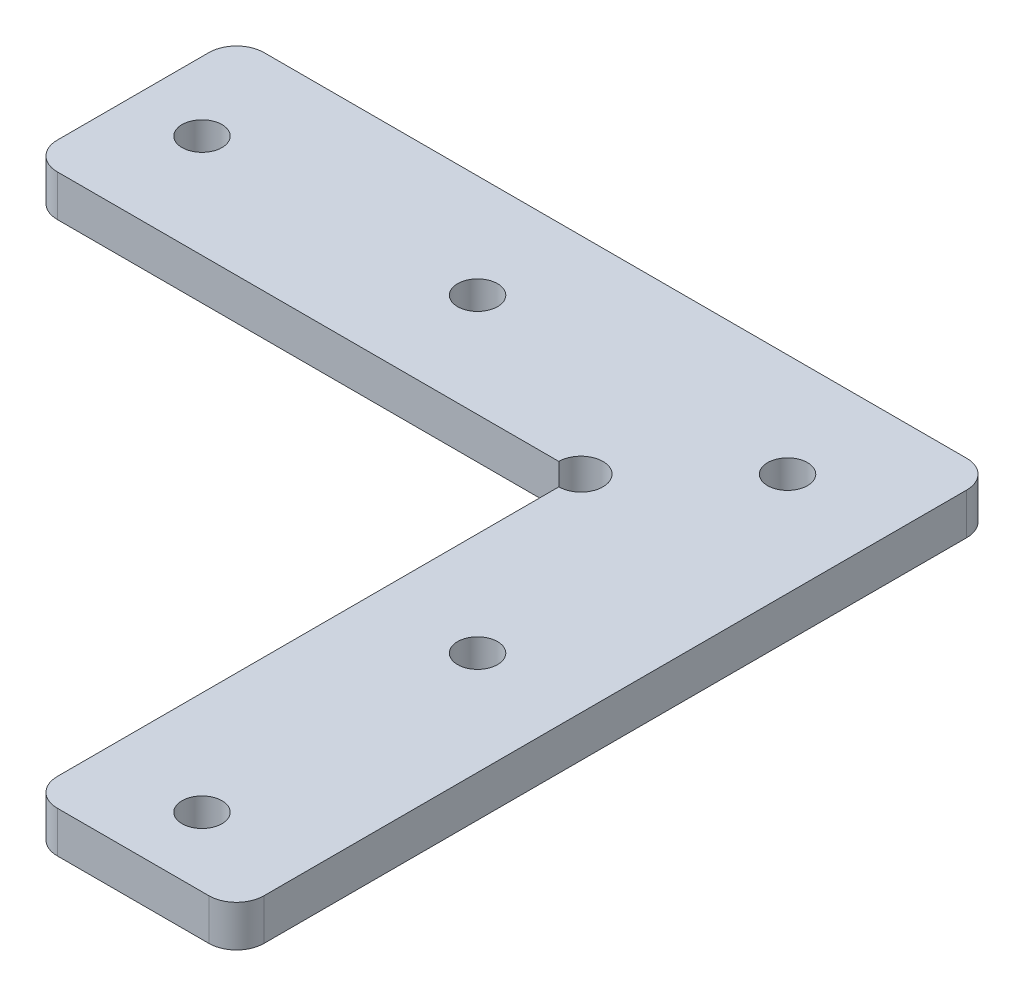
SolidWorks part; units mm, degrees
material "Thornel Mat VMA"
ref_plane "前视基准面" through (0, 0, 0) normal (0, 0, 1) x (1, 0, 0)
ref_plane "上视基准面" through (0, 0, 0) normal (0, 1, 0) x (1, 0, 0)
ref_plane "右视基准面" through (0, 0, 0) normal (1, 0, 0) x (0, 0, -1)
other "Configuration Table"
sketch "草图1" plane through (0, 0, 0) normal (0, 1, 0) x (1, 0, 0)
  line L0 (-55, 0) -> (0, 0)
  line L1 (0, 0) -> (0, -55)
  line L2 (0, -55) -> (-15, -55)
  line L3 (-15, -55) -> (-15, -15)
  line L4 (-15, -15) -> (-55, -15)
  line L5 (-55, -15) -> (-55, 0)
  line L6 (-55, -7.5) -> (0, -7.5) construction
  line L7 (-7.5, -55) -> (-7.5, 0) construction
  circle A0 centre (-7.5, -7.5) radius 1.45
  circle A1 centre (-7.5, -30) radius 1.45
  circle A2 centre (-7.5, -50) radius 1.45
  circle A3 centre (-30, -7.5) radius 1.45
  circle A4 centre (-50, -7.5) radius 1.45
  dimension "D3" = 2.9
  dimension "D4" = 2.9
  dimension "D5" = 2.9
  dimension "D9" = 2.9
  dimension "D10" = 2.9
  dimension "D11" = 22.5
  dimension "D12" = 20
  dimension "D13" = 5
  dimension "D1" = 15
  dimension "D2" = 15
  dimension "D6" = 22.5
  dimension "D7" = 20
  dimension "D8" = 5
extrude "凸台-拉伸1" add sketch "草图1" along normal blind 3
fillet "圆角1" radius 2 5 edges at (-55, 1.5, 0) (-55, 1.5, 15) (-15, 1.5, 55) (0, 1.5, 55) (0, 1.5, 0)
sketch "草图2" plane through (0, 3, 0) normal (0, 1, 0) x (1, 0, 0)
  circle A0 centre (-15, -15) radius 1.6
  dimension "D1" = 3.2
extrude "切除-拉伸1" cut sketch "草图2" against normal through all
